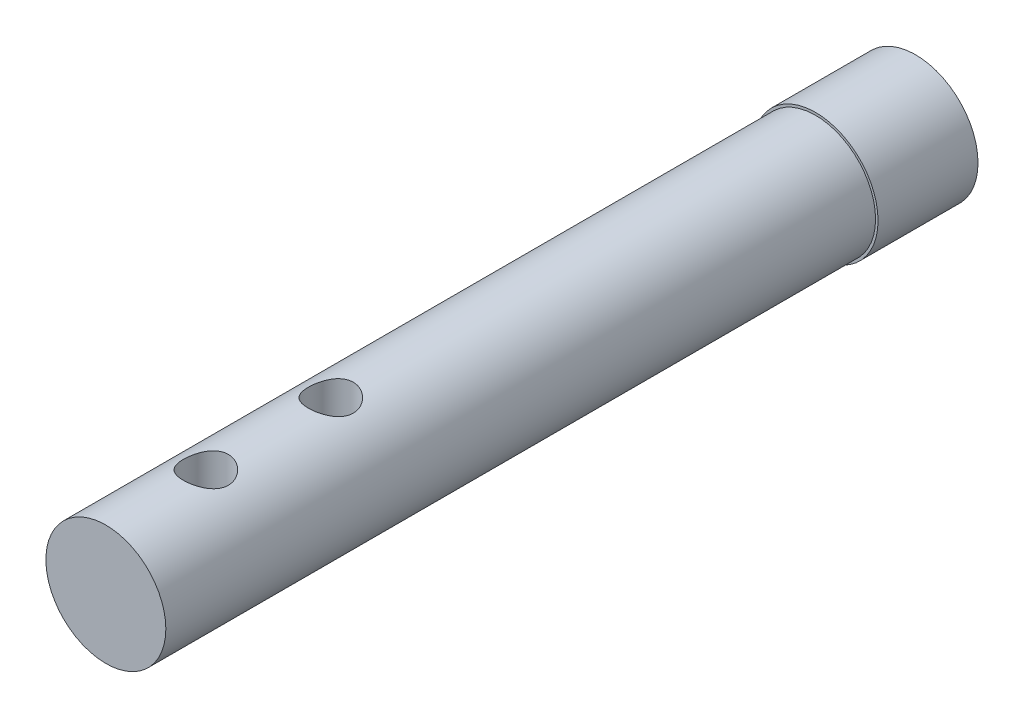
SolidWorks part; units mm, degrees
material "ASTM A36 Steel"
ref_plane "Front Plane" through (0, 0, 0) normal (0, 0, 1) x (1, 0, 0)
ref_plane "Top Plane" through (0, 0, 0) normal (0, 1, 0) x (1, 0, 0)
ref_plane "Right Plane" through (0, 0, 0) normal (1, 0, 0) x (0, 0, -1)
sketch "Sketch1" plane through (0, 0, 0) normal (0, 0, 1) x (1, 0, 0)
  circle A0 centre (0, 0) radius 10
  dimension "D1" = 20
extrude "Boss-Extrude1" add sketch "Sketch1" along normal blind 15
sketch "Sketch2" plane through (0, 0, 15) normal (0, 0, 1) x (1, 0, 0)
  circle A0 centre (0, 0) radius 12.5
  dimension "D1" = 25
extrude "Boss-Extrude2" add sketch "Sketch2" along normal blind 20
sketch "Sketch3" plane through (0, 0, 35) normal (0, 0, 1) x (1, 0, 0)
  circle A0 centre (0, 0) radius 12
  dimension "D1" = 24
extrude "Boss-Extrude3" add sketch "Sketch3" along normal blind 142
sketch "Sketch4" plane through (0, 0, 0) normal (0, 1, 0) x (1, 0, 0)
  line L0 (-12, -177) -> (12, -177) construction
  circle A0 centre (0, -157) radius 4.5
  dimension "D1" = 9
  dimension "D2" = 20
extrude "Cut-Extrude1" cut sketch "Sketch4" against normal through all both and the other way through all
sketch "Sketch5" plane through (0, 0, 0) normal (0, 1, 0) x (1, 0, 0)
  line L1 (12.5, -15) -> (-37.6297, -15)
  line L2 (12.5, -15) -> (12.5, 4.8742)
  line L3 (12.5, 4.8742) -> (-37.6297, 4.8742)
  line L4 (-37.6297, -15) -> (-37.6297, 4.8742)
extrude "Cut-Extrude2" cut sketch "Sketch5" against normal through all both and the other way through all
pattern_linear "LPattern1" count 2 spacing 25 along (0, 0, -1) of "Cut-Extrude1"
